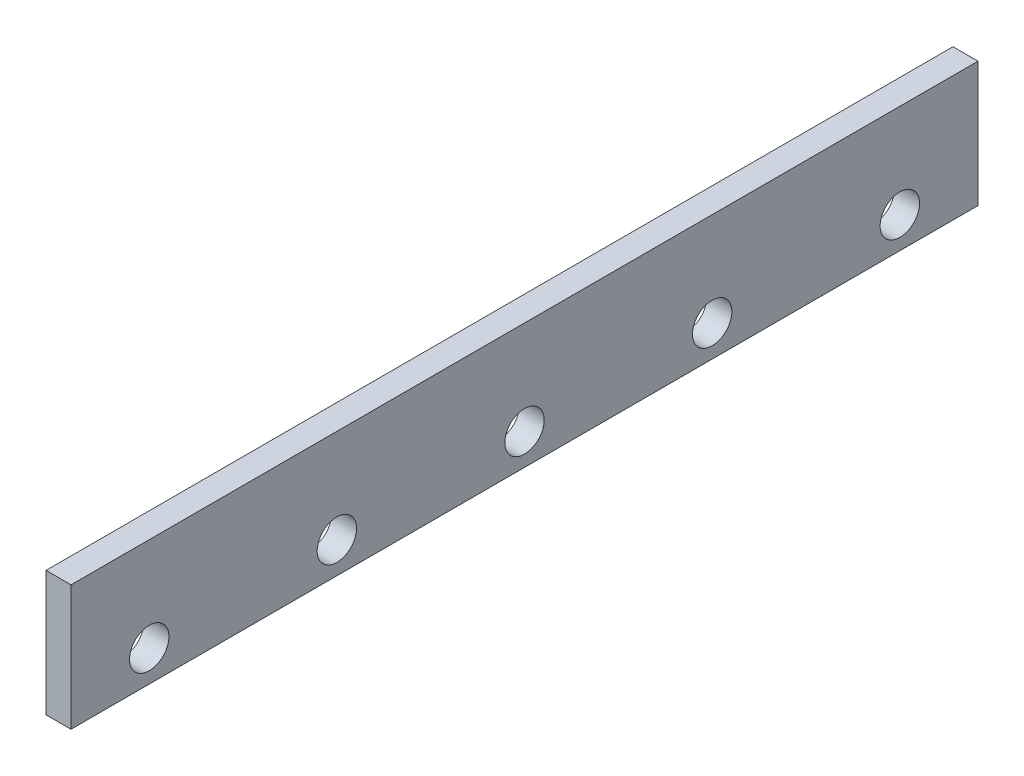
SolidWorks part; units mm, degrees
ref_plane "Front Plane" through (0, 0, 0) normal (0, 0, 1) x (1, 0, 0)
ref_plane "Top Plane" through (0, 0, 0) normal (0, 1, 0) x (1, 0, 0)
ref_plane "Right Plane" through (0, 0, 0) normal (1, 0, 0) x (0, 0, -1)
sketch "Sketch1" plane through (0, 0, 0) normal (1, 0, 0) x (0, 0, -1)
  line L1 (-290, -40) -> (290, -40)
  line L2 (-290, -40) -> (-290, 40)
  line L3 (-290, 40) -> (290, 40)
  line L4 (290, -40) -> (290, 40)
  line L5 (-290, -40) -> (290, 40) construction
  line L6 (-290, 40) -> (290, -40) construction
  circle A0 centre (-240, -20) radius 12.6
  circle A1 centre (-120, -20) radius 12.6
  circle A2 centre (0, -20) radius 12.6
  circle A3 centre (120, -20) radius 12.6
  circle A4 centre (240, -20) radius 12.6
  point P0 (0, 0)
  dimension "D7" = 25.2
  dimension "D1" = 580
  dimension "D2" = 80
  dimension "D3" = 50
  dimension "D4" = 20
  dimension "D6" = 120
  dimension "D5" = 4
extrude "Boss-Extrude1" add sketch "Sketch1" along normal mid plane 16
